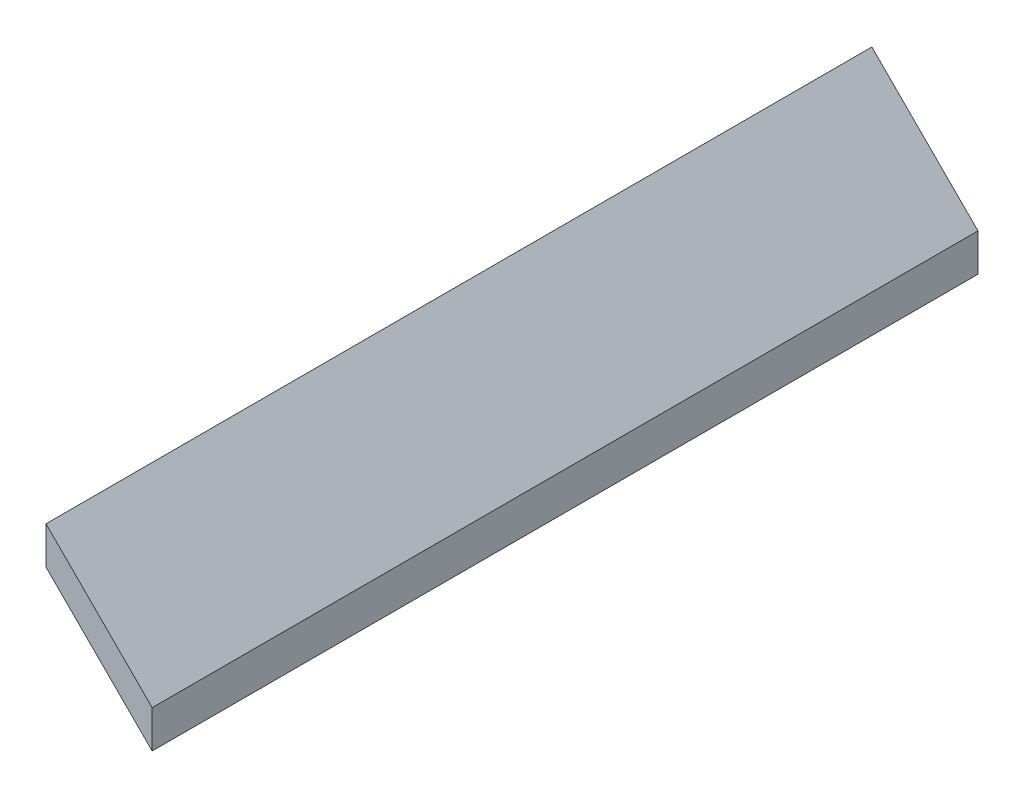
SolidWorks part; units mm, degrees
ref_plane "Front Plane" through (0, 0, 0) normal (0, 0, 1) x (1, 0, 0)
ref_plane "Top Plane" through (0, 0, 0) normal (0, 1, 0) x (1, 0, 0)
ref_plane "Right Plane" through (0, 0, 0) normal (1, 0, 0) x (0, 0, -1)
sketch "Sketch1" plane through (0, 0, 0) normal (0, 0, 1) x (1, 0, 0)
  line L0 (0, 0) -> (0, 12.7)
  line L1 (0, 12.7) -> (-35.921, 48.621)
  line L2 (-35.921, 48.621) -> (-35.921, 35.921)
  line L3 (-35.921, 35.921) -> (0, 0)
  line L4 (0, 0) -> (-61.1372, 0) construction
  dimension "D1" = 12.7
  dimension "D2" = 12.7
  dimension "D3" = 45
  dimension "D4" = 50.8
  dimension "D5" = 50.8
extrude "Boss-Extrude1" add sketch "Sketch1" along normal blind 279.4
